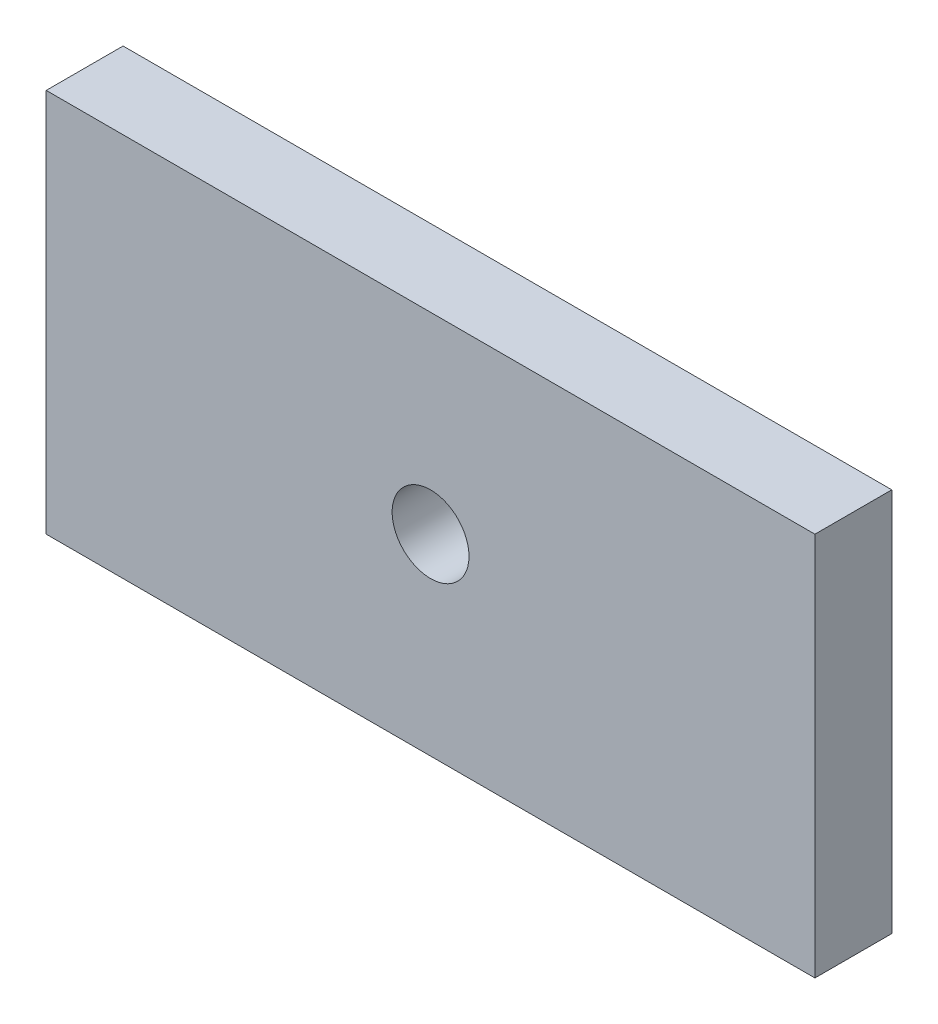
SolidWorks part; units mm, degrees
ref_plane "前视基准面" through (0, 0, 0) normal (0, 0, 1) x (1, 0, 0)
ref_plane "上视基准面" through (0, 0, 0) normal (0, 1, 0) x (1, 0, 0)
ref_plane "右视基准面" through (0, 0, 0) normal (1, 0, 0) x (0, 0, -1)
sketch "草图1" plane through (0, 0, 0) normal (0, 0, 1) x (1, 0, 0)
  line L1 (-50, -25) -> (50, -25)
  line L2 (-50, -25) -> (-50, 25)
  line L3 (-50, 25) -> (50, 25)
  line L4 (50, -25) -> (50, 25)
  line L5 (-50, -25) -> (50, 25) construction
  line L6 (-50, 25) -> (50, -25) construction
  circle A0 centre (0, 0) radius 5
  point P0 (0, 0)
  dimension "D3" = 10
  dimension "D1" = 100
  dimension "D2" = 50
extrude "凸台-拉伸1" add sketch "草图1" along normal blind 10
